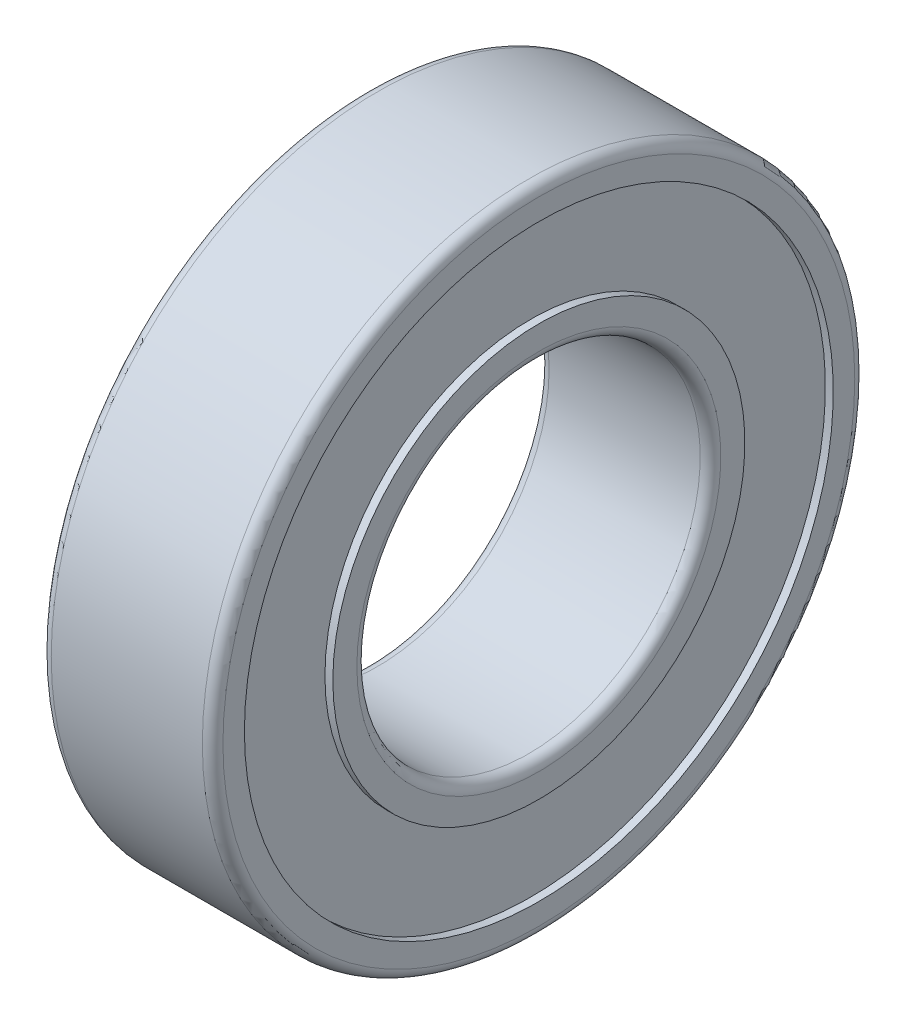
SolidWorks part; units mm, degrees
material "炭素鋼(普通)"
ref_plane "Front Plane" through (0, 0, 0) normal (0, 0, 1) x (1, 0, 0)
ref_plane "Top Plane" through (0, 0, 0) normal (0, 1, 0) x (1, 0, 0)
ref_plane "Right Plane" through (0, 0, 0) normal (1, 0, 0) x (0, 0, -1)
sketch "Sketch1" plane through (0, 0, 0) normal (0, 0, 1) x (1, 0, 0)
  line L0 (0, 0) -> (5, 0) construction
  line L1 (0, 5) -> (5, 5)
  line L2 (0, 9.5) -> (5, 9.5)
  line L3 (0, 9.5) -> (0, 8.575)
  line L4 (0, 8.575) -> (0.23, 8.575)
  line L5 (5, 9.5) -> (5, 8.575)
  line L6 (0.23, 8.575) -> (0.23, 6)
  line L7 (0.23, 6) -> (0, 6)
  line L8 (0, 6) -> (0, 5)
  line L9 (5, 8.575) -> (4.77, 8.575)
  line L10 (4.77, 8.575) -> (4.77, 6)
  line L11 (4.77, 6) -> (5, 6)
  line L12 (5, 6) -> (5, 5)
  dimension "D" = 19
  dimension "B" = 5
  dimension "D_s" = 10
  dimension "MSM_1" = 17.15
  dimension "MSM_2" = 12
  dimension "MSM_3" = 0.23
revolve "Revolve1" add sketch "Sketch1" angle 360 about L0
fillet "Fillet1" radius 0.3 2 edges at (5, 0, 9.5) (0, 0, 9.5)
fillet "Fillet2" radius 0.3 2 edges at (5, 0, 5) (0, 0, 5)
